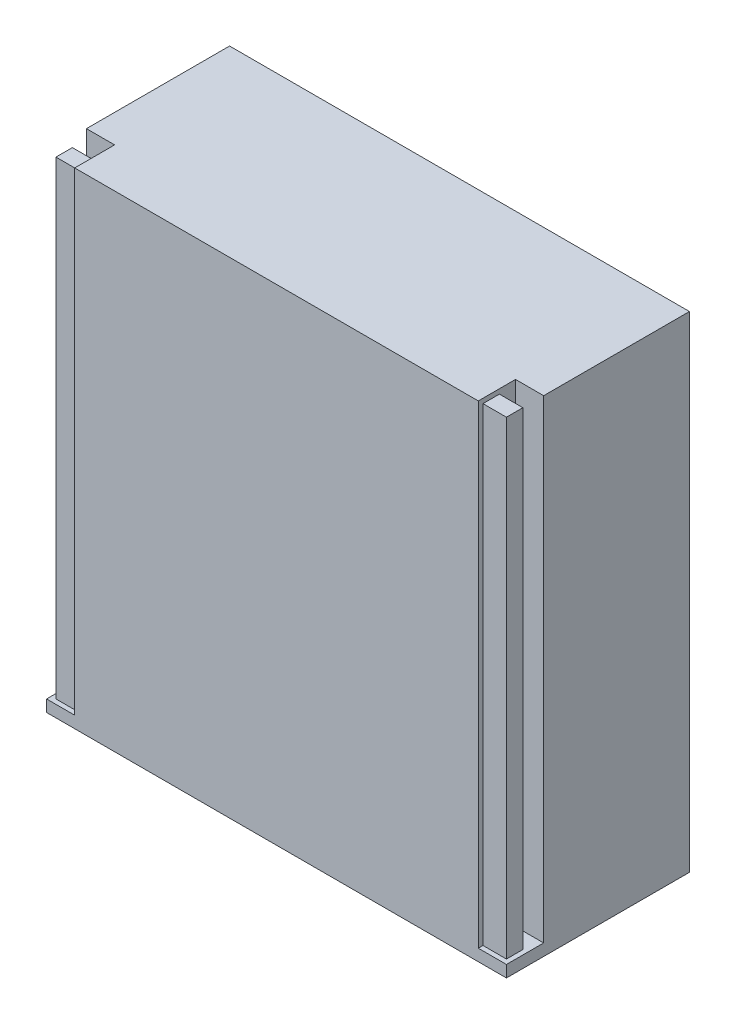
SolidWorks part; units mm, degrees
material "ABS"
ref_plane "Alzado" through (0, 0, 0) normal (0, 0, 1) x (1, 0, 0)
ref_plane "Planta" through (0, 0, 0) normal (0, 1, 0) x (1, 0, 0)
ref_plane "Vista lateral" through (0, 0, 0) normal (1, 0, 0) x (0, 0, -1)
sketch "Croquis1" plane through (0, 0, 0) normal (0, 1, 0) x (1, 0, 0)
  line L1 (-146.0596, 38) -> (49.9404, 38)
  line L2 (-146.0596, 38) -> (-146.0596, -40)
  line L3 (-146.0596, -40) -> (49.9404, -40)
  line L4 (49.9404, 38) -> (49.9404, -40)
  point P0 (0, 0)
  dimension "D1" = 78
  dimension "D2" = 196
extrude "Saliente-Extruir1" add sketch "Croquis1" along normal blind 5
sketch "Croquis2" plane through (0, 5, 0) normal (0, 1, 0) x (1, 0, 0)
  line L0 (-134.0596, -38) -> (-144.0596, -38)
  line L1 (-144.0596, -38) -> (-144.0596, -31)
  line L2 (-144.0596, -31) -> (-134.0596, -31)
  line L3 (-134.0596, -31) -> (-134.0596, -38)
  line L4 (47.9404, -31) -> (37.9404, -31)
  line L5 (37.9404, -31) -> (37.9404, -38)
  line L6 (37.9404, -38) -> (47.9404, -38)
  line L7 (47.9404, -38) -> (47.9404, -31)
  line L8 (-146.0596, -40) -> (49.9404, -40) construction
  line L9 (49.9404, -40) -> (49.9404, 38) construction
  line L10 (-146.0596, 38) -> (-146.0596, -40) construction
  dimension "D1" = 2
  dimension "D2" = 2
  dimension "D3" = 7
  dimension "D4" = 7
  dimension "D5" = 10
  dimension "D6" = 10
  dimension "D7" = 2
  dimension "D8" = 2
extrude "Saliente-Extruir2" add sketch "Croquis2" along normal blind 200
sketch "Croquis4" plane through (0, 5, 0) normal (0, 1, 0) x (1, 0, 0)
  line L0 (-146.0596, -23) -> (-134.0596, -23)
  line L1 (-146.0596, 38) -> (-146.0596, -40) construction
  line L2 (-134.0596, -23) -> (-134.0596, -40)
  line L3 (-146.0596, -40) -> (49.9404, -40) construction
  line L4 (-134.0596, -40) -> (37.9404, -40)
  line L5 (37.9404, -40) -> (37.9404, -24.1279)
  line L6 (37.9404, -24.1279) -> (49.9404, -24.1279)
  line L7 (49.9404, -40) -> (49.9404, 38) construction
  line L8 (49.9404, -24.1279) -> (49.9404, 38)
  line L9 (49.9404, 38) -> (47.9404, 38)
  line L10 (49.9404, 38) -> (-146.0596, 38) construction
  line L11 (47.9404, 38) -> (47.9404, -22.1279)
  line L12 (47.9404, -22.1279) -> (35.9404, -22.1279)
  line L13 (35.9404, -22.1279) -> (35.9404, -38)
  line L14 (35.9404, -38) -> (-132.0596, -38)
  line L15 (-132.0596, -38) -> (-132.0596, -21.1709)
  line L16 (-132.0596, -21.1709) -> (-144.0596, -21.1709)
  line L17 (-144.0596, -21.1709) -> (-144.0596, 38)
  line L18 (-144.0596, 38) -> (-146.0596, 38)
  line L19 (-146.0596, 38) -> (-146.0596, -23)
  line L20 (-134.0596, -31) -> (-144.0596, -31) construction
  line L21 (-134.0596, -38) -> (-134.0596, -31) construction
  dimension "D1" = 8
  dimension "D2" = 0
  dimension "D3" = 2
  dimension "D4" = 2
  dimension "D5" = 2
  dimension "D6" = 2
  dimension "D7" = 2
  dimension "D8" = 2
extrude "Saliente-Extruir3" add sketch "Croquis4" along normal blind 200
sketch "Croquis5" plane through (0, 205, 0) normal (0, 1, 0) x (1, 0, 0)
  line L0 (-146.0596, 38) -> (49.9404, 38)
  line L1 (49.9404, 38) -> (49.9404, -24.1279)
  line L2 (49.9404, -24.1279) -> (37.9404, -24.1279)
  line L3 (37.9404, -24.1279) -> (37.9404, -40)
  line L4 (37.9404, -40) -> (-134.0596, -40)
  line L5 (-134.0596, -40) -> (-134.0596, -23)
  line L6 (-134.0596, -23) -> (-146.0596, -23)
  line L7 (-146.0596, -23) -> (-146.0596, 38)
extrude "Saliente-Extruir4" add sketch "Croquis5" along normal blind 2
sketch "Croquis6" plane through (0, 0, 0) normal (0, -1, 0) x (1, 0, 0)
  line L0 (-48.0596, 40) -> (-48.0596, -38) construction
  line L1 (-146.0596, 40) -> (49.9404, 40) construction
  line L2 (49.9404, -38) -> (-146.0596, -38) construction
  line L3 (-83.0596, 1) -> (-13.0596, 1) construction
  line L4 (-83.0596, 1) -> (-13.0596, 1) construction
  line L5 (-83.0596, 9) -> (-13.0596, 9)
  line L6 (-83.0596, -7) -> (-13.0596, -7)
  arc A2 (-83.0596, 9) -> (-83.0596, -7) centre (-83.0596, 1) ccw
  arc A3 (-13.0596, -7) -> (-13.0596, 9) centre (-13.0596, 1) ccw
  point P6 (-48.0596, 1)
  point P9 (-48.0596, 1)
  dimension "D2" = 8
  dimension "D1" = 70
extrude "Cortar-Extruir2" cut sketch "Croquis6" against normal blind 10
